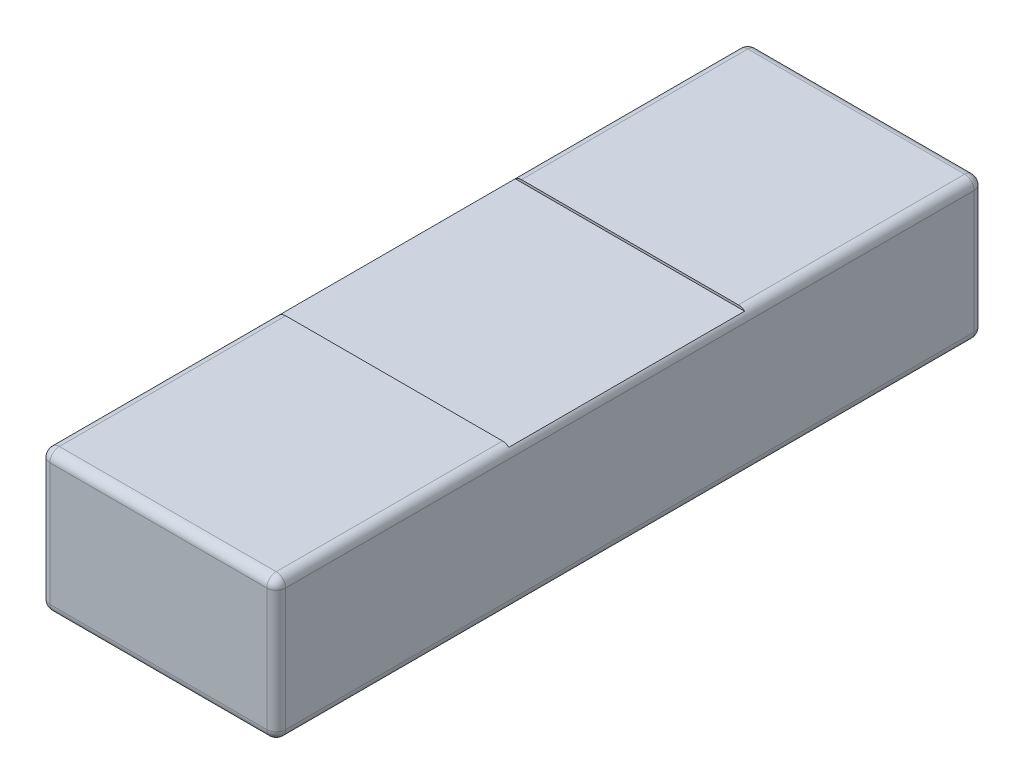
SolidWorks part; units mm, degrees
ref_plane "Front Plane" through (0, 0, 0) normal (0, 0, 1) x (1, 0, 0)
ref_plane "Top Plane" through (0, 0, 0) normal (0, 1, 0) x (1, 0, 0)
ref_plane "Right Plane" through (0, 0, 0) normal (1, 0, 0) x (0, 0, -1)
sketch "Sketch2" plane through (0, 0, 0) normal (0, 1, 0) x (1, 0, 0)
  line L1 (-25, 75) -> (25, 75)
  line L2 (-25, 75) -> (-25, -75)
  line L3 (-25, -75) -> (25, -75)
  line L4 (25, 75) -> (25, -75)
  line L5 (-25, 75) -> (25, -75) construction
  line L6 (-25, -75) -> (25, 75) construction
  point P0 (0, 0)
  dimension "D1" = 50
  dimension "D2" = 150
extrude "Boss-Extrude1" add sketch "Sketch2" along normal blind 30
fillet "Fillet1" radius 2 12 edges at (25, 0, 0) (25, 15, 75) (0, 0, 75) (25, 15, -75) (0, 0, -75) (0, 30, 75) (0, 30, -75) (25, 30, 0) (-25, 15, -75) (-25, 30, 0) (-25, 15, 75) (-25, 0, 0)
sketch "Sketch3" plane through (0, 30, 0) normal (0, 1, 0) x (1, 0, 0)
  line L6 (-49.8697, 25) -> (49.8697, 25)
  line L7 (-49.8697, 25) -> (-49.8697, -25)
  line L8 (-49.8697, -25) -> (49.8697, -25)
  line L9 (49.8697, 25) -> (49.8697, -25)
  line L10 (-49.8697, 25) -> (49.8697, -25) construction
  line L11 (-49.8697, -25) -> (49.8697, 25) construction
  point P0 (0, 0)
  dimension "D1" = 50
extrude "Cut-Extrude1" cut sketch "Sketch3" against normal blind 0.5
sketch "Sketch4" plane through (0, 0, 0) normal (0, -1, 0) x (1, 0, 0)
  line L1 (-42.2838, 25) -> (42.2838, 25)
  line L2 (-42.2838, 25) -> (-42.2838, -25)
  line L3 (-42.2838, -25) -> (42.2838, -25)
  line L4 (42.2838, 25) -> (42.2838, -25)
  line L5 (-42.2838, 25) -> (42.2838, -25) construction
  line L6 (-42.2838, -25) -> (42.2838, 25) construction
  point P0 (0, 0)
  dimension "D1" = 50
extrude "Cut-Extrude2" cut sketch "Sketch4" against normal blind 0.5
